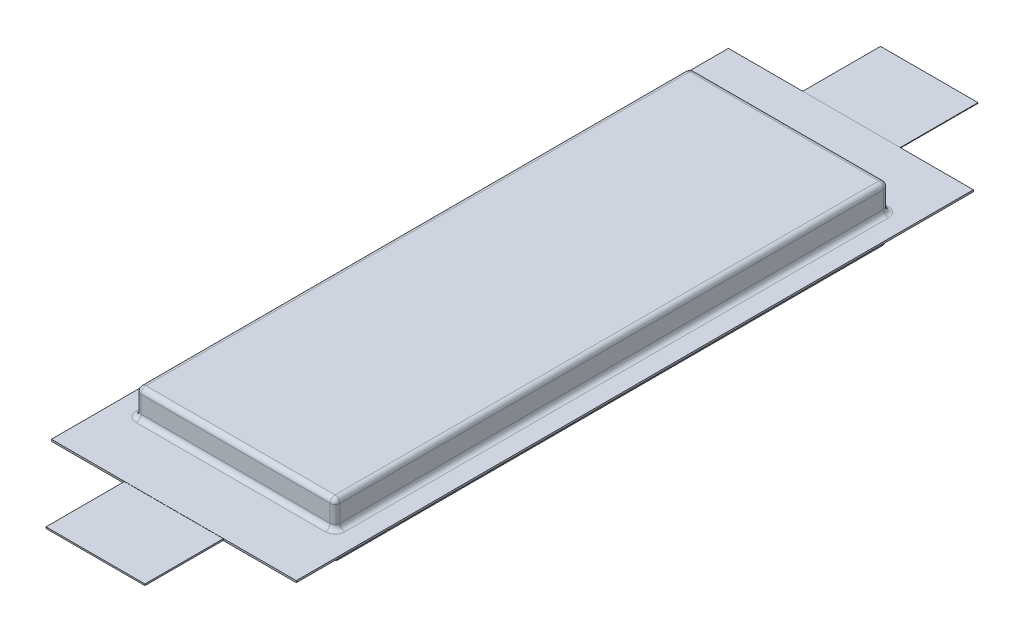
SolidWorks part; units mm, degrees
material "Zinc AC41A Alloy, As Cast"
ref_plane "Front Plane" through (0, 0, 0) normal (0, 0, 1) x (1, 0, 0)
ref_plane "Top Plane" through (0, 0, 0) normal (0, 1, 0) x (1, 0, 0)
ref_plane "Right Plane" through (0, 0, 0) normal (1, 0, 0) x (0, 0, -1)
sketch "Sketch1" plane through (0, 0, 0) normal (0, 1, 0) x (1, 0, 0)
  line L1 (0, 0) -> (40.6, 0)
  line L2 (0, 0) -> (0, 113)
  line L3 (0, 113) -> (40.6, 113)
  line L4 (40.6, 0) -> (40.6, 113)
extrude "Boss-Extrude2" add sketch "Sketch1" along normal blind 11.4
sketch "Sketch3" plane through (0, 0, 0) normal (0, 0, 1) x (1, 0, 0)
  line L0 (0, 11.4) -> (0, 0) construction
  line L1 (0, 5.7) -> (-4.7, 5.7)
  line L2 (0, 5.7) -> (0, 5.69)
  line L3 (0, 5.69) -> (-4.7, 5.69)
  line L4 (-4.7, 5.7) -> (-4.7, 5.69)
extrude "Boss-Extrude3" add sketch "Sketch3" along normal blind 1 separate body
sketch "Sketch4" plane through (0, 5.7, 0) normal (0, 1, 0) x (1, 0, 0)
  line L1 (-4.7, -12.6) -> (45.3, -12.6)
  line L2 (-4.7, -12.6) -> (-4.7, 125.6)
  line L3 (-4.7, 125.6) -> (45.3, 125.6)
  line L4 (45.3, -12.6) -> (45.3, 125.6)
extrude "Boss-Extrude4" add sketch "Sketch4" along normal blind 0.185 and the other way blind 0.185
sketch "Sketch5" plane through (0, 0, 12.6) normal (0, 0, 1) x (1, 0, 0)
  line L0 (20.3, 5.7) -> (20.3, 5.85)
  line L1 (20.3, 5.85) -> (30.4, 5.85)
  line L2 (30.4, 5.85) -> (30.4, 5.55)
  line L3 (30.4, 5.55) -> (10.2, 5.55)
  line L4 (10.2, 5.55) -> (10.2, 5.85)
  line L5 (10.2, 5.85) -> (20.3, 5.85)
extrude "Boss-Extrude5" add sketch "Sketch5" along normal blind 16
sketch "Sketch6" plane through (0, 0, -125.6) normal (0, 0, -1) x (-1, 0, 0)
  line L0 (-20.3, 5.7) -> (-20.3, 5.765)
  line L1 (-20.3, 5.765) -> (-10.35, 5.765)
  line L2 (-10.35, 5.765) -> (-10.35, 5.635)
  line L3 (-10.35, 5.635) -> (-30.25, 5.635)
  line L4 (-30.25, 5.635) -> (-30.25, 5.765)
  line L5 (-30.25, 5.765) -> (-20.3, 5.765)
extrude "Boss-Extrude6" add sketch "Sketch6" along normal blind 16 contours L1 L2 L3 L4 L5
fillet "Fillet1" radius 1 24 edges at (20.3, 5.515, 0) (20.3, 5.885, 0) (20.3, 5.885, -113) (40.6, 2.7575, 0) (40.6, 5.515, -56.5) (0, 5.515, -56.5) (0, 2.7575, 0) (40.6, 2.7575, -113) (20.3, 5.515, -113) (0, 2.7575, -113) (0, 8.6425, -113) (0, 8.6425, 0) (0, 5.885, -56.5) (40.6, 8.6425, 0) (40.6, 8.6425, -113) (40.6, 5.885, -56.5) (20.3, 0, 0) (40.6, 0, -56.5) (20.3, 0, -113) (0, 0, -56.5) (20.3, 11.4, -113) (40.6, 11.4, -56.5) (20.3, 11.4, 0) (0, 11.4, -56.5)
ref_plane "Centre" through (0, 0, -56.5) normal (0, 0, -1) x (-1, 0, 0)
ref_plane "Plane2" through (20.3, 0, 0) normal (-1, 0, 0) x (0, 0, 1)
ref_plane "Plane3" through (0, 5.7, 0) normal (0, 1, 0) x (1, 0, 0)
